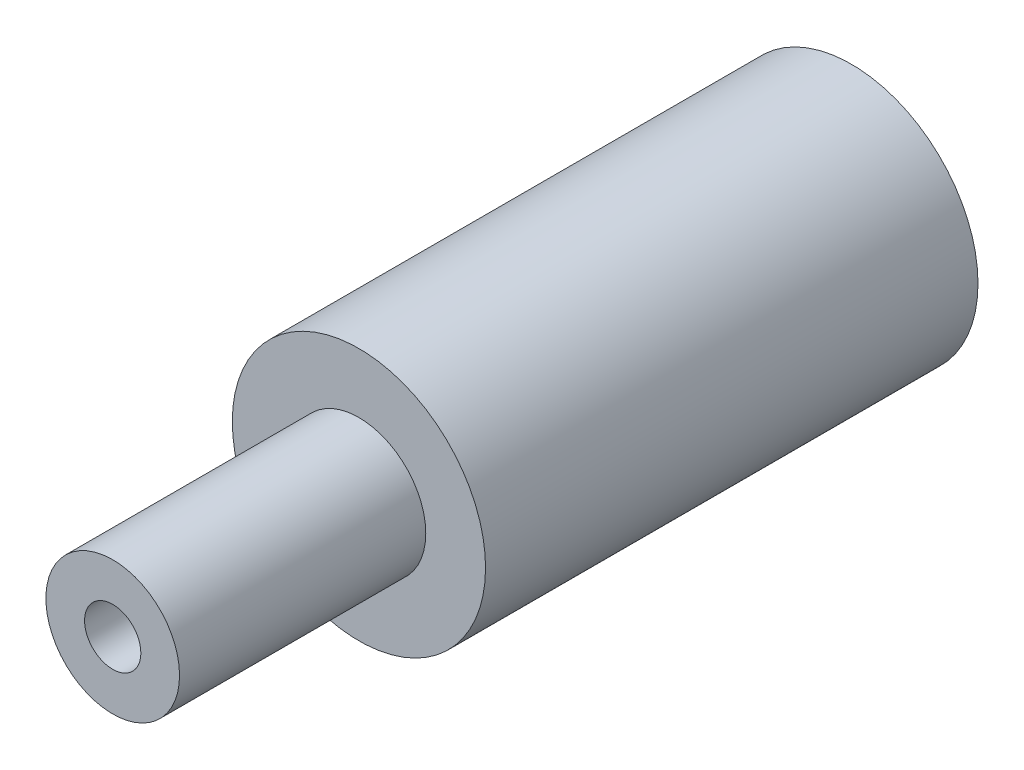
SolidWorks part; units mm, degrees
material "1023 Carbon Steel Sheet (SS)"
ref_plane "Front Plane" through (0, 0, 0) normal (0, 0, 1) x (1, 0, 0)
ref_plane "Top Plane" through (0, 0, 0) normal (0, 1, 0) x (1, 0, 0)
ref_plane "Right Plane" through (0, 0, 0) normal (1, 0, 0) x (0, 0, -1)
sketch "Sketch1" plane through (0, 0, 0) normal (0, 0, 1) x (1, 0, 0)
  circle A0 centre (0, 0) radius 18
  dimension "D1" = 36
extrude "Boss-Extrude1" add sketch "Sketch1" along normal blind 70
sketch "Sketch2" plane through (0, 0, 70) normal (0, 0, 1) x (1, 0, 0)
  circle A0 centre (0, 0) radius 2.5
  dimension "D1" = 5
extrude "Boss-Extrude2" add sketch "Sketch2" along normal blind 16
sketch "Sketch3" plane through (0, 0, 70) normal (0, 0, 1) x (1, 0, 0)
  circle A0 centre (0, 0) radius 9.5
  circle A1 centre (0, 0) radius 2.5
  dimension "D1" = 19
extrude "Boss-Extrude3" add sketch "Sketch3" along normal blind 25
sketch "Sketch4" plane through (0, 0, 95) normal (0, 0, 1) x (1, 0, 0)
  circle A0 centre (0, 0) radius 9.5
  circle A1 centre (0, 0) radius 4
  dimension "D1" = 8
extrude "Boss-Extrude4" add sketch "Sketch4" along normal blind 10
